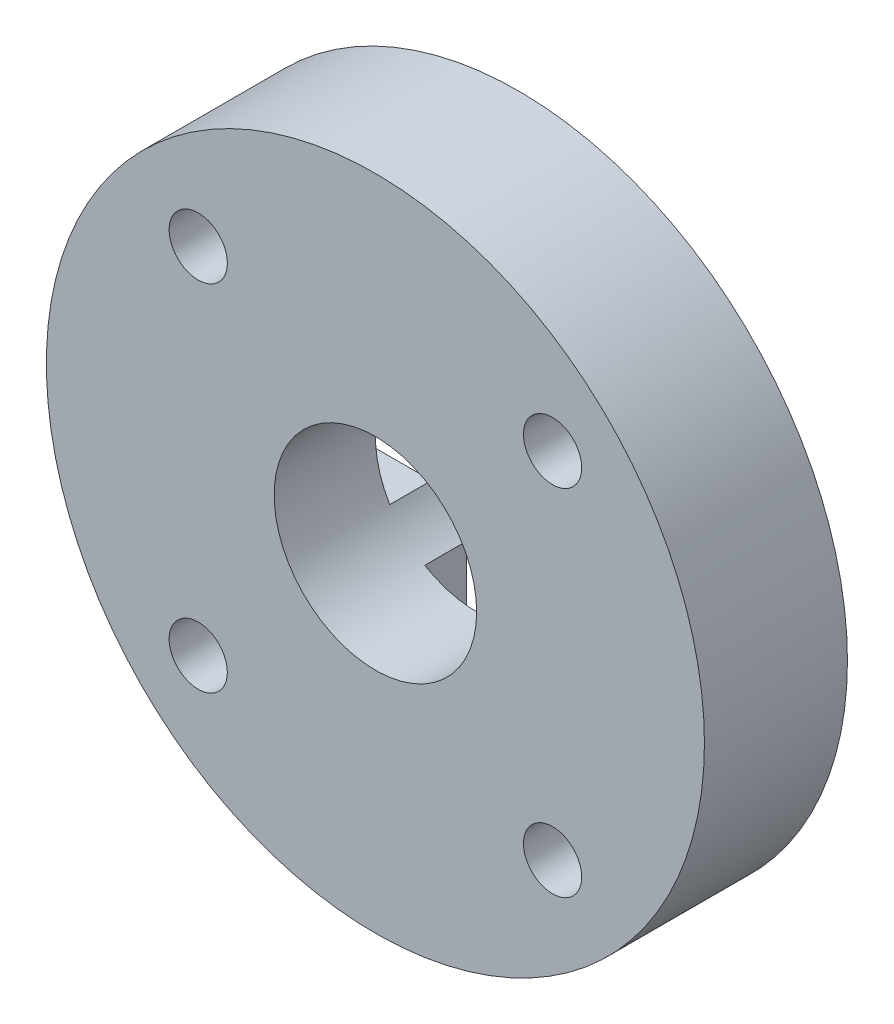
SolidWorks part; units mm, degrees
ref_plane "Front Plane" through (0, 0, 0) normal (0, 0, 1) x (1, 0, 0)
ref_plane "Top Plane" through (0, 0, 0) normal (0, 1, 0) x (1, 0, 0)
ref_plane "Right Plane" through (0, 0, 0) normal (1, 0, 0) x (0, 0, -1)
sketch "Trial_load_plate_profile" plane through (0, 0, 0) normal (0, 0, 1) x (1, 0, 0)
  circle A0 centre (0, 0) radius 13
  circle A1 centre (0, 0) radius 4
  dimension "D1" = 26
  dimension "D2" = 8
extrude "Trial_load_plate" add sketch "Trial_load_plate_profile" along normal blind 4
sketch "Captured_horn_key_boss_profile" plane through (0, 0, 0) normal (0, 0, 1) x (1, 0, 0)
  circle A0 centre (0, 0) radius 13
  dimension "D1" = 26
extrude "Captured_horn_key_boss" add sketch "Captured_horn_key_boss_profile" along normal blind 1.65 from offset 1.65
sketch "Stock_horn_pocket_Hub" plane through (0, 0, 0) normal (0, 0, 1) x (1, 0, 0)
  circle A0 centre (0, 0) radius 3.5
  dimension "D1" = 7
extrude "Key_pocket_Hub" cut sketch "Stock_horn_pocket_Hub" along normal blind 1.65 from offset 1.65
sketch "Stock_horn_pocket_Horizontal" plane through (0, 0, 0) normal (0, 0, 1) x (1, 0, 0)
  line L1 (-8.15, -2.05) -> (8.15, -2.05)
  line L2 (-8.15, -2.05) -> (-8.15, 2.05)
  line L3 (-8.15, 2.05) -> (8.15, 2.05)
  line L4 (8.15, -2.05) -> (8.15, 2.05)
  dimension "D1" = 16.3
  dimension "D2" = 4.1
  dimension "D3" = 8.15
  dimension "D4" = 2.05
extrude "Key_pocket_Horizontal" cut sketch "Stock_horn_pocket_Horizontal" along normal blind 1.65 from offset 1.65
sketch "Stock_horn_pocket_Vertical" plane through (0, 0, 0) normal (0, 0, 1) x (1, 0, 0)
  line L1 (-2.05, -8.15) -> (2.05, -8.15)
  line L2 (-2.05, -8.15) -> (-2.05, 8.15)
  line L3 (-2.05, 8.15) -> (2.05, 8.15)
  line L4 (2.05, -8.15) -> (2.05, 8.15)
  dimension "D1" = 4.1
  dimension "D2" = 16.3
  dimension "D3" = 2.05
  dimension "D4" = 8.15
extrude "Key_pocket_Vertical" cut sketch "Stock_horn_pocket_Vertical" along normal blind 1.65 from offset 1.65
sketch "Stock_horn_pocket_Rounded_tips" plane through (0, 0, 0) normal (0, 0, 1) x (1, 0, 0)
  circle A0 centre (8.15, 0) radius 2.05
  circle A1 centre (-8.15, 0) radius 2.05
  circle A2 centre (0, 8.15) radius 2.05
  circle A3 centre (0, -8.15) radius 2.05
  dimension "D1" = 4.1
  dimension "D2" = 4.1
  dimension "D3" = 4.1
  dimension "D4" = 4.1
  dimension "D5" = 8.15
  dimension "D6" = 8.15
  dimension "D7" = 8.15
  dimension "D8" = 8.15
extrude "Key_pocket_Rounded_tips" cut sketch "Stock_horn_pocket_Rounded_tips" along normal blind 1.65 from offset 1.65
sketch "Unmodified_horn_capture_M2_profile" plane through (0, 0, 0) normal (0, 0, 1) x (1, 0, 0)
  circle A0 centre (7, 7) radius 1.15
  circle A1 centre (-7, 7) radius 1.15
  circle A2 centre (-7, -7) radius 1.15
  circle A3 centre (7, -7) radius 1.15
  dimension "D1" = 2.3
  dimension "D2" = 2.3
  dimension "D3" = 2.3
  dimension "D4" = 2.3
  dimension "D5" = 7
  dimension "D6" = 7
  dimension "D7" = 7
  dimension "D8" = 7
extrude "Unmodified_horn_capture_M2" cut sketch "Unmodified_horn_capture_M2_profile" along normal through all from offset 50
sketch "Horn_center_hub_clearance" plane through (0, 0, 0) normal (0, 0, 1) x (1, 0, 0)
  circle A0 centre (0, 0) radius 4
  dimension "D1" = 8
extrude "Hub_clearance_in_key_boss_only" cut sketch "Horn_center_hub_clearance" along normal blind 1.65 from offset 1.65
